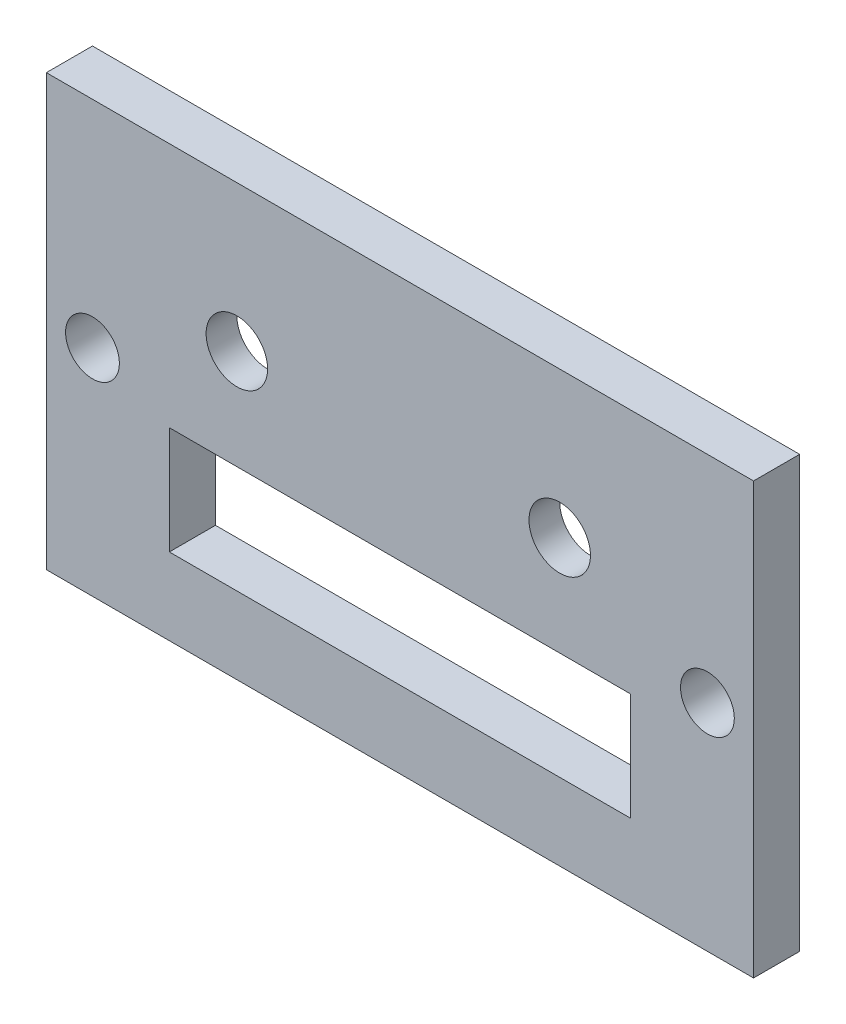
SolidWorks part; units mm, degrees
ref_plane "Alzado" through (0, 0, 0) normal (0, 0, 1) x (1, 0, 0)
ref_plane "Planta" through (0, 0, 0) normal (0, 1, 0) x (1, 0, 0)
ref_plane "Vista lateral" through (0, 0, 0) normal (1, 0, 0) x (0, 0, -1)
sketch "Croquis1" plane through (0, 0, 0) normal (0, 0, 1) x (1, 0, 0)
  line L0 (-10.6077, 1.5) -> (10.3923, 1.5) construction
  line L1 (-15, 6) -> (15, 6)
  line L2 (-15, 6) -> (-15, -5)
  line L3 (-15, -5) -> (15, -5)
  line L4 (15, 6) -> (15, -5)
  circle A0 centre (-10.6077, 1.5) radius 2
  circle A1 centre (10.3923, 1.5) radius 2
  point P4 (-10.6077, 1.5)
  point P6 (10.3923, 1.5)
  dimension "D8" = 4
  dimension "D9" = 4
  dimension "D1" = 30
  dimension "D2" = 15
  dimension "D3" = 11
  dimension "D4" = 5
  dimension "D5" = 21
  dimension "D6" = 10.5
  dimension "D7" = 6.5
extrude "union-imu" add sketch "Croquis1" along normal blind 2
sketch "Croquis2" plane through (0, 0, 2) normal (0, 0, 1) x (1, 0, 0)
  line L0 (-20, -3) -> (20, -3) construction
  line L1 (-15, 6) -> (-15, -5) construction
  line L2 (-23, -4) -> (-23, 11)
  line L3 (-23, 11) -> (23, 11)
  line L4 (23, 11) -> (23, -4)
  line L6 (15, -5) -> (15, 6) construction
  line L7 (15, 6) -> (-15, 6) construction
  line L8 (-23, -4) -> (-23, -17)
  line L9 (-23, -17) -> (23, -17)
  line L10 (23, -17) -> (23, -4)
  line L11 (-15, -5) -> (-15, -12)
  line L12 (-15, -12) -> (15, -12)
  line L13 (15, -12) -> (15, -5)
  line L14 (-15, -5) -> (15, -5) construction
  circle A0 centre (-20, -3) radius 1.75
  circle A1 centre (20, -3) radius 1.75
  line M9 (-15, 6) -> (-15, -5)
  line M11 (15, -5) -> (15, 6)
  line M12 (15, 6) -> (-15, 6)
  dimension "D6" = 3.5
  dimension "D7" = 3.5
  dimension "D8" = 14
  dimension "D9" = 3
  dimension "D10" = 3
  dimension "D1" = 8
  dimension "D2" = 8
  dimension "D3" = 5
  dimension "D4" = 7
  dimension "D5" = 5
extrude "union-carcasa" add sketch "Croquis2" against normal blind 3 contours L9 L10 L4 L3 L2 L8 A1 A0 L13 L12 L11 M9 M12 M11
